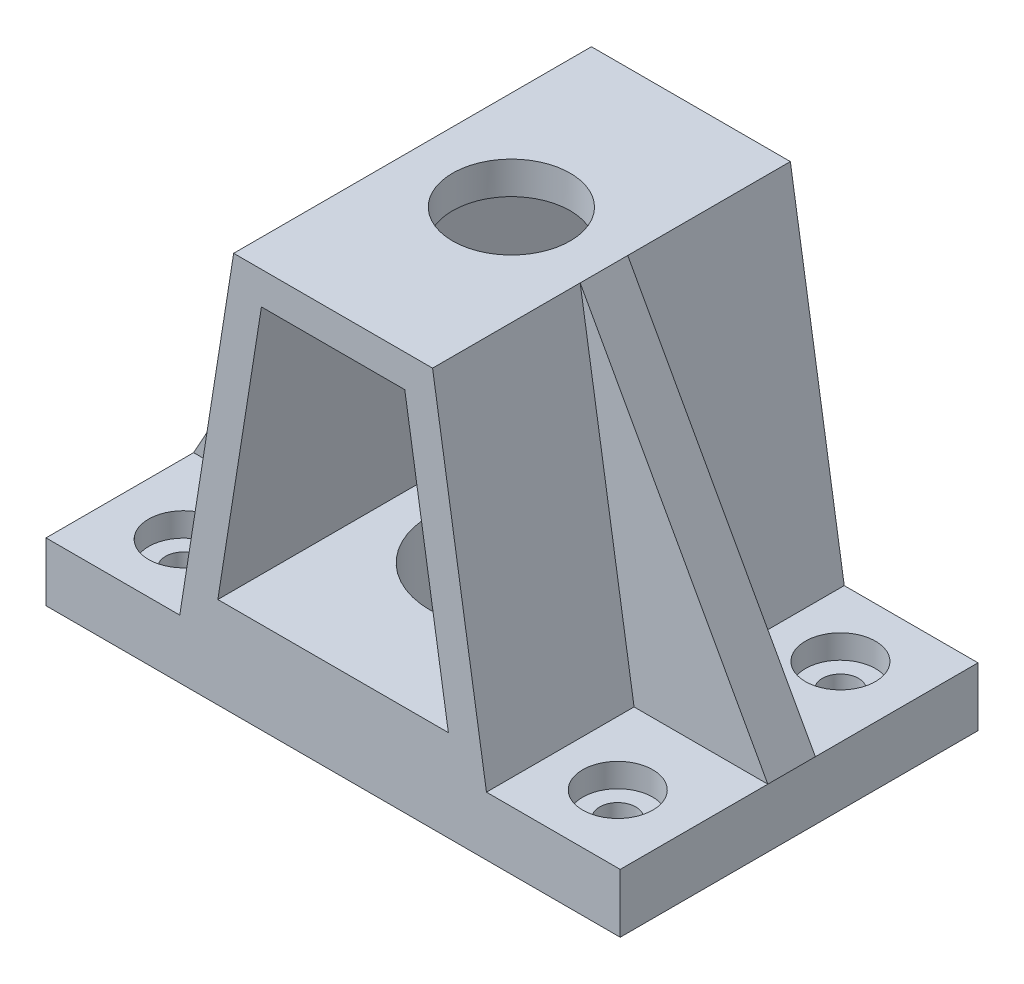
SolidWorks part; units mm, degrees
ref_plane "Front Plane" through (0, 0, 0) normal (0, 0, 1) x (1, 0, 0)
ref_plane "Top Plane" through (0, 0, 0) normal (0, 1, 0) x (1, 0, 0)
ref_plane "Right Plane" through (0, 0, 0) normal (1, 0, 0) x (0, 0, -1)
sketch "Sketch3" plane through (0, 0, 0) normal (0, 1, 0) x (1, 0, 0)
  line L1 (-58.293, -36.322) -> (58.293, -36.322)
  line L2 (-58.293, -36.322) -> (-58.293, 36.322)
  line L3 (-58.293, 36.322) -> (58.293, 36.322)
  line L4 (58.293, -36.322) -> (58.293, 36.322)
  line L5 (-58.293, -36.322) -> (58.293, 36.322) construction
  line L6 (-58.293, 36.322) -> (58.293, -36.322) construction
  point P0 (0, 0)
  dimension "D1" = 116.586
  dimension "D2" = 72.644
extrude "Boss-Extrude1" add sketch "Sketch3" along normal mid plane 11.938
sketch "Sketch4" plane through (0, 0, 0) normal (0, 0, 1) x (1, 0, 0)
  line L0 (-31.1355, 5.969) -> (-20.193, 75.057)
  line L1 (-58.293, 5.969) -> (58.293, 5.969) construction
  line L2 (-20.193, 75.057) -> (20.193, 75.057)
  line L3 (20.193, 75.057) -> (31.1355, 5.969)
  line L4 (31.1355, 5.969) -> (-31.1355, 5.969)
  line L5 (-58.293, 5.969) -> (-31.1355, 5.969) construction
  line L6 (31.1355, 5.969) -> (58.293, 5.969) construction
  line L7 (-23.4032, 12.573) -> (-14.5527, 68.453)
  line L8 (-14.5527, 68.453) -> (14.5527, 68.453)
  line L9 (14.5527, 68.453) -> (23.4032, 12.573)
  line L10 (23.4032, 12.573) -> (-23.4032, 12.573)
  dimension "D1" = 40.386
  dimension "D2" = 99
  dimension "D3" = 69.088
  dimension "D4" = 6.604
extrude "Boss-Extrude2" add sketch "Sketch4" along normal mid plane 72.644
ref_plane "Plane1" through (0, 0, -3.302) normal (0, 0, -1) x (-1, 0, 0)
sketch "Sketch5" plane through (0, 0, -3.302) normal (0, 0, -1) x (-1, 0, 0)
  line L0 (-20.193, 75.057) -> (-58.293, 5.969)
  line L1 (-58.293, 5.969) -> (-31.1355, 5.969)
  line L2 (-31.1355, 5.969) -> (-20.193, 75.057)
extrude "Boss-Extrude3" add sketch "Sketch5" against normal blind 9.652
mirror "Mirror1" about plane through (0, 0, 0) normal (1, 0, 0) of "Boss-Extrude3"
sketch "Sketch6" plane through (0, 75.057, 0) normal (0, 1, 0) x (1, 0, 0)
  circle A0 centre (-0.127, 0) radius 11.938
  dimension "D3" = 23.876
  dimension "D1" = 20.32
  dimension "D2" = 36.322
extrude "Cut-Extrude1" cut sketch "Sketch6" against normal up to next
sketch "Sketch7" plane through (0, 5.969, 0) normal (0, 1, 0) x (1, 0, 0)
  line L0 (-44.069, -22.5984) -> (-44.069, 22.6136)
  line L1 (-44.069, 22.6136) -> (44.069, 22.6136)
  line L2 (44.069, 22.6136) -> (44.069, -22.5984)
  line L3 (44.069, -22.5984) -> (-44.069, -22.5984)
  line L4 (-44.069, 22.6136) -> (44.069, -22.5984) construction
  line L5 (-44.069, -22.5984) -> (44.069, 22.6136) construction
  line L6 (-44.069, -22.5984) -> (-58.293, -22.5984) construction
  line L7 (-58.293, -6.35) -> (-58.293, -36.322) construction
  line L8 (44.069, -22.5984) -> (58.293, -22.5984) construction
  line L9 (58.293, -36.322) -> (58.293, -6.35) construction
  line L10 (-44.069, 22.6136) -> (-44.7142, 36.322) construction
  line L11 (-31.1355, 36.322) -> (-58.293, 36.322) construction
  line L12 (-44.069, -22.5984) -> (-44.069, -36.322) construction
  line L13 (-58.293, -36.322) -> (-31.1355, -36.322) construction
  dimension "D1" = 88.138
  dimension "D2" = 45.212
hole_wizard "CBORE for #00 Binding Head Machine Screw1" positions "3DSketch1" profile "Sketch8" counterbore size "#00" standard "ANSI Inch" end condition through all
sketch3d "3DSketch1"
  point P0 (-44.069, 5.969, 22.5984)
  point P3 (44.069, 5.969, 22.5984)
  point P6 (44.069, 5.969, -22.6136)
  point P9 (-44.069, 5.969, -22.6136)
sketch "Sketch8" plane through (-44.069, 5.969, 22.5984) normal (1, 0, 0) x (0, 0, 1)
  line L0 (0, 0) -> (0, 11.938)
  line L1 (0, 11.938) -> (3.683, 11.938)
  line L3 (3.683, 11.938) -> (3.683, 4.826)
  line L4 (3.683, 4.826) -> (7.112, 4.826)
  line L5 (7.112, 4.826) -> (7.112, 0)
  line L7 (7.112, 0) -> (0, 0)
  line L11 (0, -6.35) -> (0, 107.95) construction
  dimension "Thru Hole Dia." = 7.366
  dimension "Thru Hole Depth" = 11.938
  dimension "C'Bore Dia." = 14.224
  dimension "C'Bore Depth" = 4.826
sketch "Sketch9" plane through (0, 12.573, 0) normal (0, 1, 0) x (1, 0, 0)
  circle A0 centre (0, 0) radius 16.637
  dimension "D1" = 33.274
extrude "Cut-Extrude2" cut sketch "Sketch9" against normal through all
